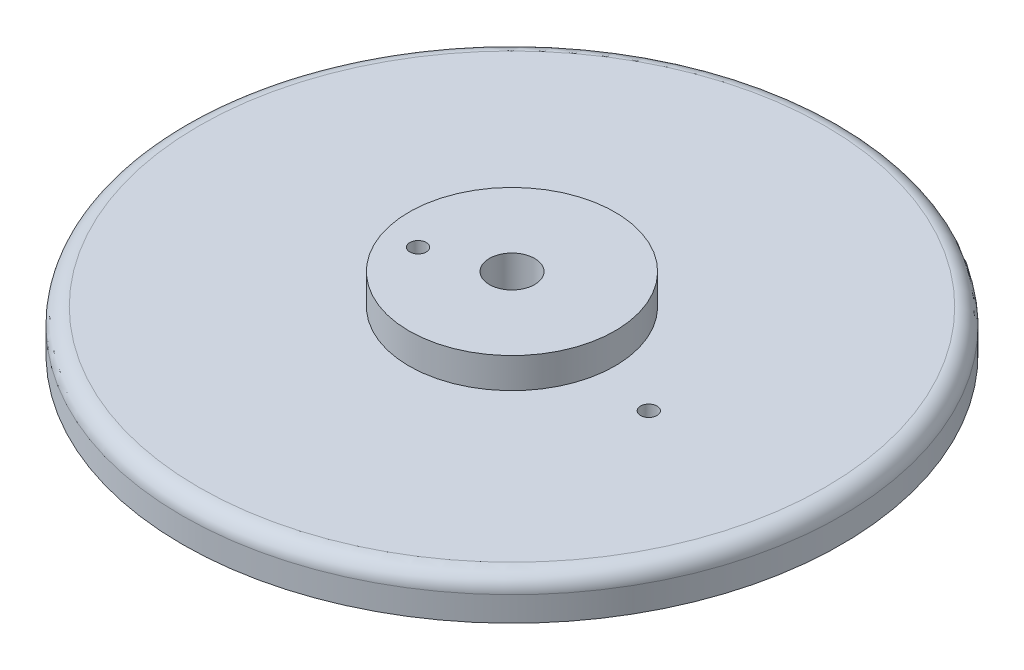
SolidWorks part; units mm, degrees
ref_plane "Front Plane" through (0, 0, 0) normal (0, 0, 1) x (1, 0, 0)
ref_plane "Top Plane" through (0, 0, 0) normal (0, 1, 0) x (1, 0, 0)
ref_plane "Right Plane" through (0, 0, 0) normal (1, 0, 0) x (0, 0, -1)
sketch "Sketch2" plane through (0, 0, 0) normal (0, 1, 0) x (1, 0, 0)
  circle A0 centre (0, 0) radius 40
  circle A1 centre (0, 0) radius 2.75
  dimension "D1" = 80
  dimension "D2" = 5.5
extrude "Boss-Extrude1" add sketch "Sketch2" along normal blind 5
fillet "Fillet1" radius 2 1 edges at (0, 5, 40)
sketch "Sketch3" plane through (0, 5, 0) normal (0, 1, 0) x (1, 0, 0)
  circle A0 centre (0, 0) radius 2.75 construction
  circle A1 centre (0, 0) radius 2.75
  circle A2 centre (0, 0) radius 12.5
  dimension "D1" = 25
extrude "Boss-Extrude2" add sketch "Sketch3" along normal blind 3.69
sketch "Sketch4" plane through (0, 8.69, 0) normal (0, 1, 0) x (1, 0, 0)
  line L0 (56.0911, 0) -> (-56.0911, 0) construction
  line L1 (0, 0) -> (0, -45.4879) construction
  circle A0 centre (-8.25, -3.15) radius 1
  circle A1 centre (19.25, -2.65) radius 1
  point P6 (0, 0)
  dimension "D1" = 2
  dimension "D2" = 2
  dimension "D3" = 8.25
  dimension "D4" = 3.15
  dimension "D5" = 19.25
  dimension "D6" = 2.65
extrude "Cut-Extrude1" cut sketch "Sketch4" against normal through all
